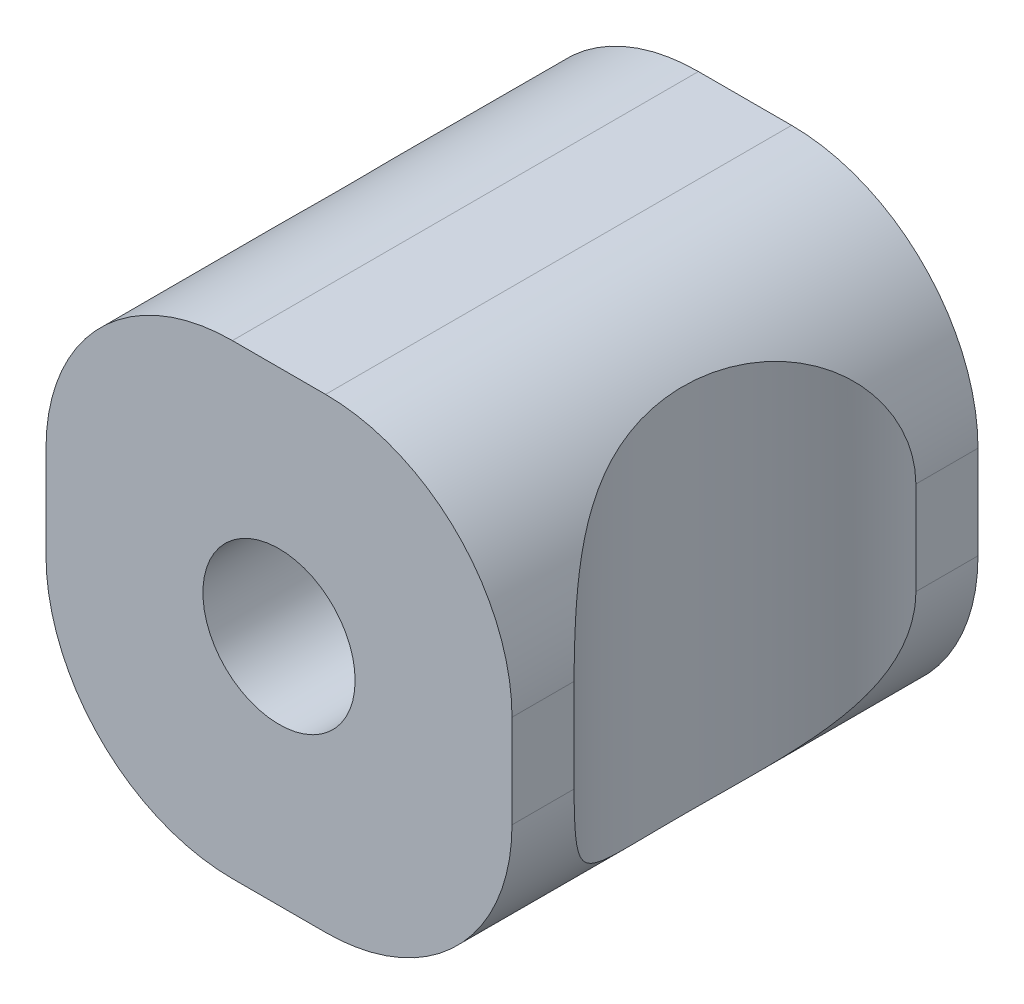
SolidWorks part; units mm, degrees
ref_plane "Přední rovina" through (0, 0, 0) normal (0, 0, 1) x (1, 0, 0)
ref_plane "Horní rovina" through (0, 0, 0) normal (0, 1, 0) x (1, 0, 0)
ref_plane "Pravá rovina" through (0, 0, 0) normal (1, 0, 0) x (0, 0, -1)
sketch "Base sketch" plane through (0, 0, 0) normal (0, 0, 1) x (1, 0, 0)
  line L1 (-7.5, 7.5) -> (7.5, 7.5)
  line L2 (-7.5, 7.5) -> (-7.5, -7.5)
  line L3 (-7.5, -7.5) -> (7.5, -7.5)
  line L4 (7.5, 7.5) -> (7.5, -7.5)
  line L5 (-7.5, 7.5) -> (7.5, -7.5) construction
  line L6 (-7.5, -7.5) -> (7.5, 7.5) construction
  point P0 (0, 0)
  dimension "D1" = 15
extrude "Base" add sketch "Base sketch" along normal blind 15
sketch "Nut hole sketch" plane through (0, 0, 15) normal (0, 0, 1) x (1, 0, 0)
  circle A0 centre (0, 0) radius 2.45
  dimension "D1" = 4.9
extrude "Nut hole" cut sketch "Nut hole sketch" against normal blind 10
fillet "Rounding" radius 6 4 edges at (-7.5, -7.5, 7.5) (7.5, -7.5, 7.5) (7.5, 7.5, 7.5) (-7.5, 7.5, 7.5)
sketch "Thumb hole sketch" plane through (0, -7.5, 0) normal (0, -1, 0) x (1, 0, 0)
  line L0 (0, 0) -> (-7.5, 0)
  line L1 (-1.5, 0) -> (1.5, 0) construction
  line L2 (0, 0) -> (0, 15)
  line L3 (-1.5, 15) -> (1.5, 15) construction
  line L4 (0, 15) -> (-7.5, 15)
  line L5 (-7.5, 15) -> (-7.5, 0)
  arc A0 (-7.5, 2) -> (-7.5, 13) centre (-14.0625, 7.5) ccw
  point P11 (-5.5, 7.5)
  dimension "D1" = 7.5
  dimension "D2" = 2
  dimension "D3" = 2
  dimension "D4" = 2
extrude "Thumb hole" cut sketch "Thumb hole sketch" against normal through all contours L5 A0
pattern_circular "Kruhové pole1" count 2 every 180 about axis through (0, 0, 7.5) along (0, 1, 0) of "Thumb hole"
